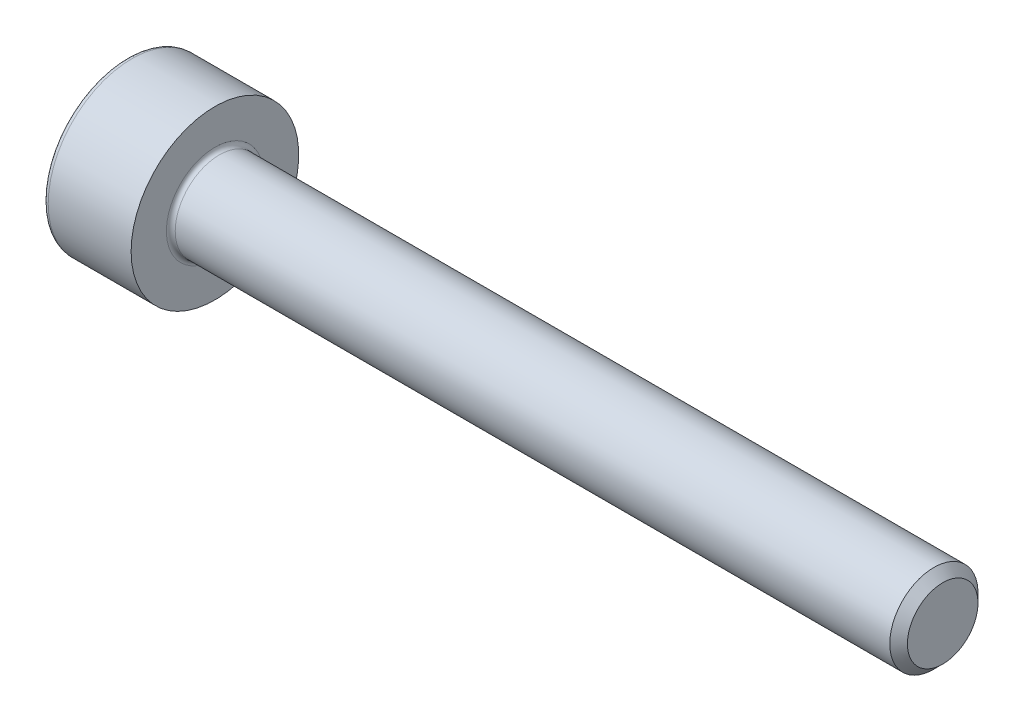
SolidWorks part; units mm, degrees
ref_plane "Front Plane" through (0, 0, 0) normal (0, 0, 1) x (1, 0, 0)
ref_plane "Top Plane" through (0, 0, 0) normal (0, 1, 0) x (1, 0, 0)
ref_plane "Right Plane" through (0, 0, 0) normal (1, 0, 0) x (0, 0, -1)
sketch "Sketch1" plane through (0, 0, 0) normal (0, 0, 1) x (1, 0, 0)
  line L0 (0, 0) -> (0, 1.9)
  line L1 (0, 1.9) -> (2, 1.9)
  line L2 (2, 1.9) -> (2, 0)
  line L3 (0, 0) -> (4.2799, 0) construction
  line L4 (2, 0) -> (18.5, 0)
  line L5 (18.5, 0) -> (18.5, 1)
  line L6 (18.5, 1) -> (2, 1)
  dimension "D1" = 16.5
revolve "Revolve1" add sketch "Sketch1" angle 360 about L3
fillet "Fillet1" radius 0.1 1 edges at (2, 0, 1)
fillet "Fillet2" radius 0.12 1 edges at (0, 0, 1.9)
chamfer "Chamfer1" distance 0.2 angle 45 1 edges at (18.5, 0, 1)
sketch "Sketch2" plane through (0, 0, 0) normal (-1, 0, 0) x (0, 0, 1)
  line L1 (0, 0.866) -> (-0.75, 0.433)
  line L2 (-0.75, 0.433) -> (-0.75, -0.433)
  line L3 (-0.75, -0.433) -> (0, -0.866)
  line L4 (0, -0.866) -> (0.75, -0.433)
  line L5 (0.75, -0.433) -> (0.75, 0.433)
  line L6 (0.75, 0.433) -> (0, 0.866)
  circle A0 centre (0, 0) radius 0.75 construction
extrude "Extrude1" cut sketch "Sketch2" against normal blind 1
